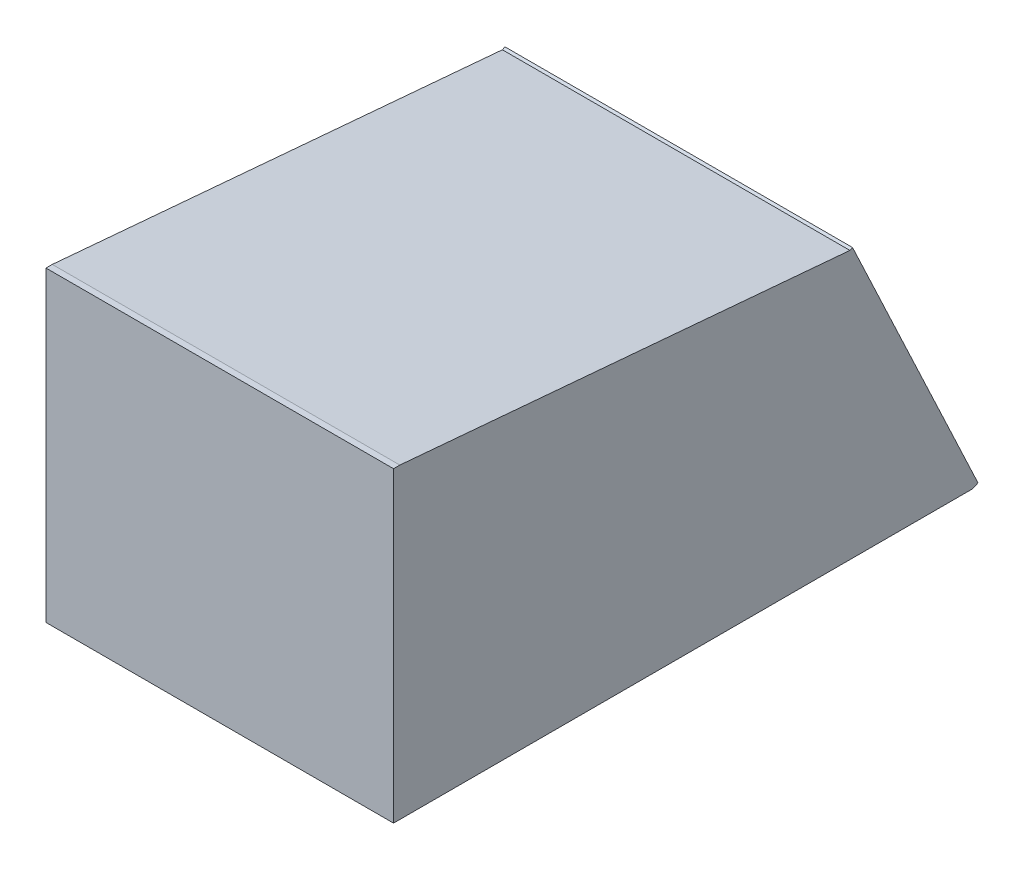
SolidWorks part; units mm, degrees
material "PP Film"
ref_plane "Front" through (0, 0, 0) normal (0, 0, 1) x (1, 0, 0)
ref_plane "Top" through (0, 0, 0) normal (0, 1, 0) x (1, 0, 0)
ref_plane "Right" through (0, 0, 0) normal (1, 0, 0) x (0, 0, -1)
sketch "Sketch1" plane through (0, 0, 0) normal (1, 0, 0) x (0, 0, -1)
  line L0 (-247.5, 130) -> (-247.5, -130)
  line L1 (-247.5, -130) -> (247.5, -130)
  line L2 (247.5, -130) -> (141.0322, 96.196)
  line L3 (141.0322, 96.196) -> (-247.5, 130)
  point P4 (0, -130)
  point P5 (-247.5, 0)
  dimension "D1" = 260
  dimension "D2" = 495
  dimension "D3" = 250
  dimension "D4" = 390
extrude "Boss-Extrude1" add sketch "Sketch1" along normal blind 5
ref_plane "Plane1" through (-180, 0, 0) normal (-1, 0, 0) x (0, 0, 1)
sketch "Sketch2" plane through (0, 107.6515, -9.3662) normal (0, 0.9962, -0.0867) x (1, 0, 0)
  line L1 (5, 132.1635) -> (-295, 132.1635)
  line L2 (5, 132.1635) -> (5, -257.8365)
  line L3 (5, -257.8365) -> (-295, -257.8365)
  line L4 (-295, 132.1635) -> (-295, -257.8365)
  point P5 (0, 0)
  dimension "D1" = 300
extrude "Boss-Extrude2" add sketch "Sketch2" along normal blind 5
sketch "Sketch3" plane through (-295, 0, 0) normal (-1, 0, 0) x (0, 0, 1)
  line L4 (247.5, 130) -> (-141.0322, 96.196)
  line L5 (-141.0322, 96.196) -> (-247.5, -130)
  line L6 (-247.5, -130) -> (247.5, -130)
  line L7 (247.5, -130) -> (247.5, 130)
  line L8 (247.5, 130) -> (-141.0322, 96.196)
  line L9 (-141.0322, 96.196) -> (-247.5, -130)
  line L10 (-247.5, -130) -> (247.5, -130)
  line L11 (247.5, -130) -> (247.5, 130)
  dimension "D1" = 0
extrude "Boss-Extrude3" add sketch "Sketch3" against normal blind 5
sketch "Sketch4" plane through (0, 71.7894, -152.5201) normal (0, 0.4259, -0.9048) x (-1, 0, 0)
  line L1 (-5, -223.025) -> (295, -223.025)
  line L2 (-5, -223.025) -> (-5, 31.2973)
  line L3 (-5, 31.2973) -> (295, 31.2973)
  line L4 (295, -223.025) -> (295, 31.2973)
extrude "Boss-Extrude4" add sketch "Sketch4" along normal blind 5
sketch "Sketch7" plane through (0, 0, 247.5) normal (0, 0, 1) x (1, 0, 0)
  line L1 (5, -130) -> (-295, -130)
  line L2 (5, -130) -> (5, 134.9812)
  line L3 (5, 134.9812) -> (-295, 134.9812)
  line L4 (-295, -130) -> (-295, 134.9812)
extrude "Boss-Extrude7" add sketch "Sketch7" along normal blind 5 and the other way up to surface other way up to face at (-145, 131.6604, 247.3555)
